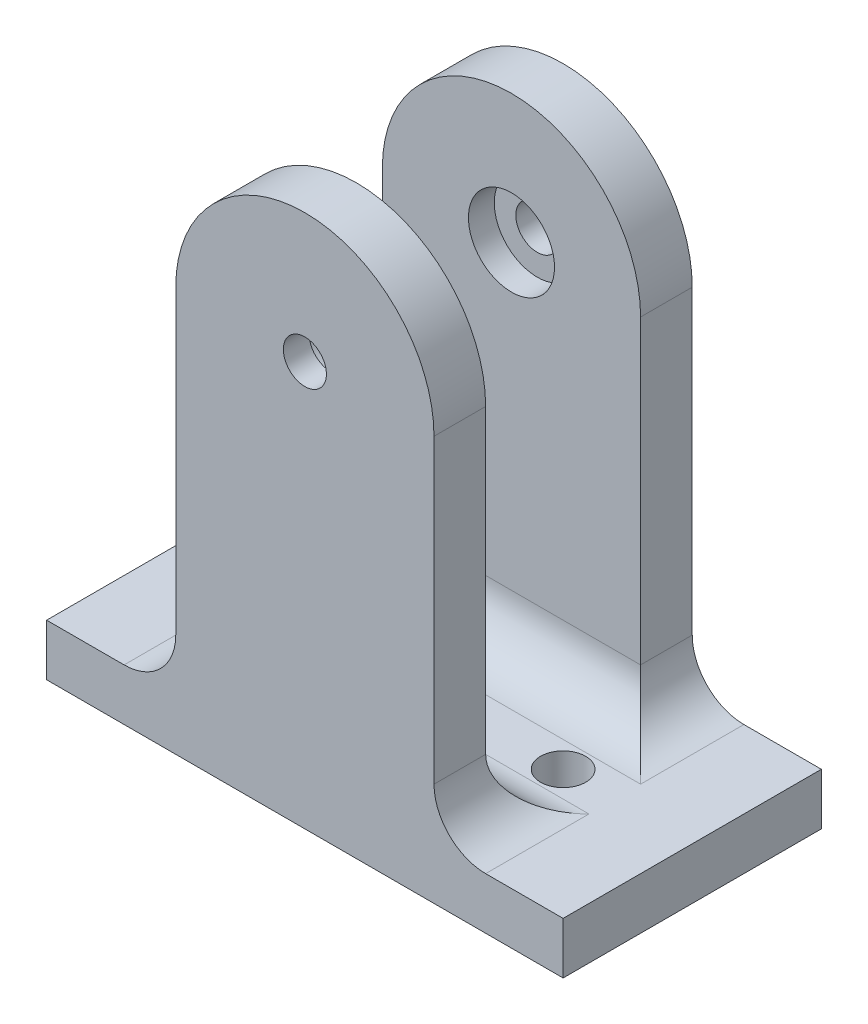
SolidWorks part; units mm, degrees
ref_plane "Front Plane" through (0, 0, 0) normal (0, 0, 1) x (1, 0, 0)
ref_plane "Top Plane" through (0, 0, 0) normal (0, 1, 0) x (1, 0, 0)
ref_plane "Right Plane" through (0, 0, 0) normal (1, 0, 0) x (0, 0, -1)
sketch "Sketch1" plane through (0, 0, 0) normal (0, 1, 0) x (1, 0, 0)
  line L0 (0, 19.05) -> (76.2, 19.05) construction
  line L1 (0, 0) -> (76.2, 0)
  line L2 (0, 0) -> (0, 38.1)
  line L3 (0, 38.1) -> (76.2, 38.1)
  line L4 (76.2, 0) -> (76.2, 38.1)
  line L5 (38.1, 38.1) -> (38.1, 0) construction
  circle A0 centre (19.05, 19.05) radius 3.3274
  circle A1 centre (57.15, 19.05) radius 3.3274
  dimension "D3" = 6.6548
  dimension "D1" = 76.2
  dimension "D2" = 38.1
  dimension "D4" = 19.05
extrude "Boss-Extrude1" add sketch "Sketch1" along normal blind 7.62
ref_plane "Plane1" through (0, 0, -19.05) normal (0, 0, 1) x (1, 0, 0)
sketch "Sketch2" plane through (0, 0, 0) normal (0, 0, 1) x (1, 0, 0)
  line L5 (19.05, 7.62) -> (19.05, 59.69)
  line L6 (0, 7.62) -> (76.2, 7.62) construction
  line L7 (57.15, 7.62) -> (57.15, 59.69)
  line L8 (19.05, 7.62) -> (57.15, 7.62)
  line L9 (0, 7.62) -> (0, 0) construction
  arc A2 (19.05, 59.69) -> (57.15, 59.69) centre (38.1, 59.69) cw
  circle A3 centre (38.1, 59.69) radius 3.175
  dimension "D2" = 19.05
  dimension "D3" = 19.05
  dimension "D4" = 6.35
  dimension "D1" = 52.07
extrude "Boss-Extrude2" add sketch "Sketch2" against normal blind 7.62
fillet "Fillet1" radius 7.62 3 edges at (38.1, 7.62, -7.62) (19.05, 7.62, -3.81) (57.15, 7.62, -3.81)
sketch "Sketch3" plane through (0, 0, -7.62) normal (0, 0, -1) x (-1, 0, 0)
  circle A1 centre (-38.1, 59.69) radius 6.35
  dimension "D1" = 12.7
extrude "Cut-Extrude1" cut sketch "Sketch3" against normal blind 3.81
mirror "Mirror2" about plane through (0, 0, -19.05) normal (0, 0, 1) of "Boss-Extrude2", "Fillet1", "Cut-Extrude1"
